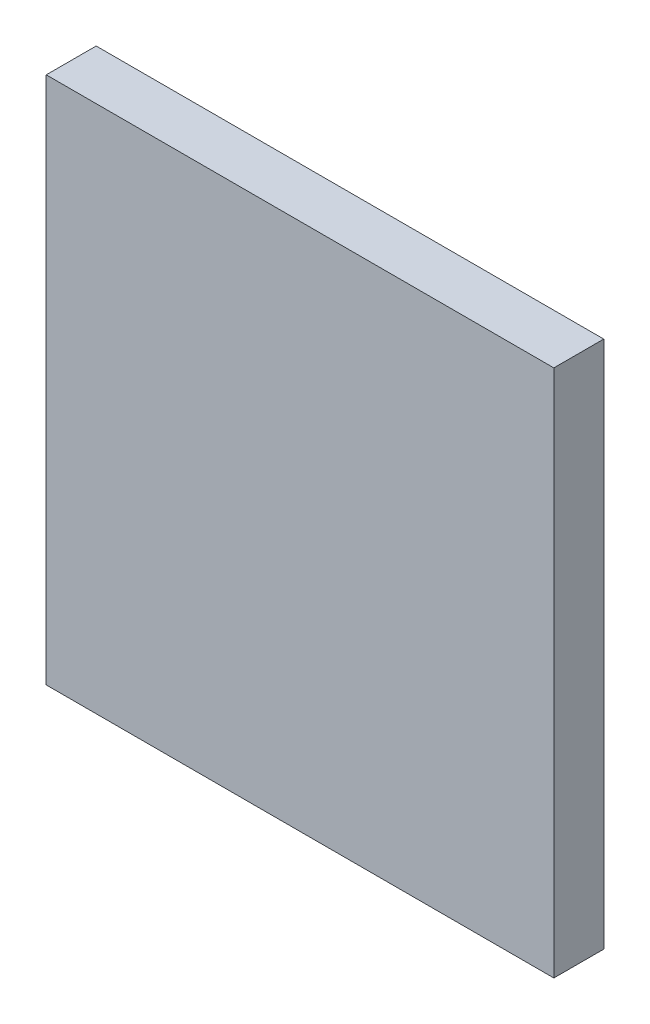
SolidWorks part; units mm, degrees
ref_plane "前视基准面" through (0, 0, 0) normal (0, 0, 1) x (1, 0, 0)
ref_plane "上视基准面" through (0, 0, 0) normal (0, 1, 0) x (1, 0, 0)
ref_plane "右视基准面" through (0, 0, 0) normal (1, 0, 0) x (0, 0, -1)
sketch "草图1" plane through (0, 0, 0) normal (0, 0, 1) x (1, 0, 0)
  line L1 (-122, 127) -> (122, 127)
  line L2 (-122, 127) -> (-122, -127)
  line L3 (-122, -127) -> (122, -127)
  line L4 (122, 127) -> (122, -127)
  line L5 (-122, 127) -> (122, -127) construction
  line L6 (-122, -127) -> (122, 127) construction
  point P0 (0, 0)
  dimension "D1" = 244
  dimension "D2" = 254
extrude "凸台-拉伸1" add sketch "草图1" along normal blind 24
sketch "草图4" plane through (0, 0, 0) normal (0, 0, 1) x (1, 0, 0)
  line L0 (0, -13.2) -> (0, 13.2) construction
  line L1 (13.2, 0) -> (-13.2, 0) construction
  circle A0 centre (80, 30) radius 4.5
  circle A1 centre (-80, 30) radius 4.5
  circle A2 centre (-80, -30) radius 4.5
  circle A3 centre (80, -30) radius 4.5
  point P12 (0, 0)
  dimension "D1" = 160
  dimension "D2" = 60
sketch "草图5" plane through (0, 0, 24) normal (0, 0, 1) x (1, 0, 0)
  line L0 (-115.6442, 105) -> (140.5977, 105) construction
  line L1 (0, -13.2) -> (0, 13.2) construction
  line L2 (13.2, 0) -> (-13.2, 0) construction
  line L3 (-115.6442, -105) -> (140.5977, -105) construction
  circle A0 centre (-80, 105) radius 6
  circle A1 centre (0, 105) radius 6
  circle A2 centre (80, 105) radius 6
  circle A3 centre (80, -105) radius 6
  circle A4 centre (0, -105) radius 6
  circle A5 centre (-80, -105) radius 6
  point P20 (0, 0)
  dimension "D1" = 160
  dimension "D2" = 210
ref_point "A_IN"
ref_point "B_IN"
ref_point "C_IN"
ref_point "A_OUT"
ref_point "B_OUT"
ref_point "C_OUT"
